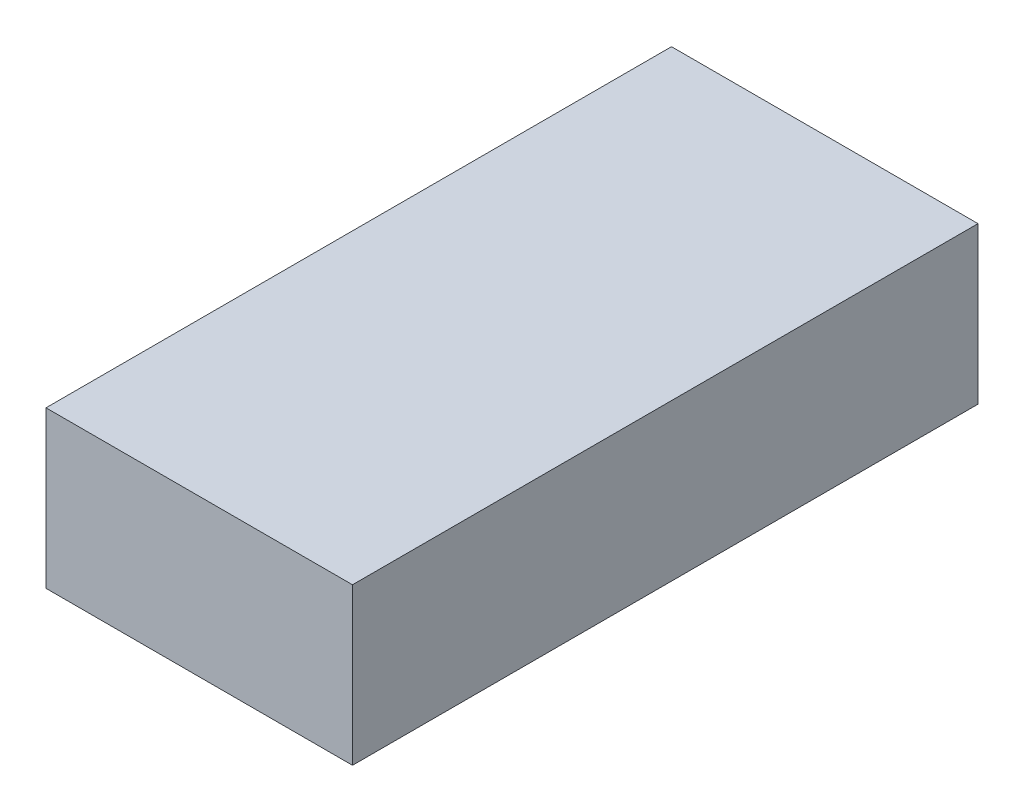
SolidWorks part; units mm, degrees
ref_plane "Спереди" through (0, 0, 0) normal (0, 0, 1) x (1, 0, 0)
ref_plane "Сверху" through (0, 0, 0) normal (0, 1, 0) x (1, 0, 0)
ref_plane "Справа" through (0, 0, 0) normal (1, 0, 0) x (0, 0, -1)
sketch "Эскиз1" plane through (0, 0, 0) normal (0, 0, 1) x (1, 0, 0)
  line L1 (-49, 25) -> (49, 25)
  line L2 (-49, 25) -> (-49, -25)
  line L3 (-49, -25) -> (49, -25)
  line L4 (49, 25) -> (49, -25)
  line L5 (-49, 25) -> (49, -25) construction
  line L6 (-49, -25) -> (49, 25) construction
  point P0 (0, 0)
  dimension "D1" = 98
  dimension "D2" = 50
extrude "База" add sketch "Эскиз1" along normal mid plane 200
hole_wizard "Отверстие обработанное метчиком M41" positions "Эскиз4" profile "Эскиз5" tap size "M4" standard "ISO"
sketch "Эскиз4" plane through (0, -25, 0) normal (0, -1, 0) x (-1, 0, 0)
  line L0 (25, -75) -> (0, -75) construction
  line L1 (0, -75) -> (-25, -75) construction
  line L2 (-25, -75) -> (-25, 0) construction
  line L3 (-25, 0) -> (-25, 75) construction
  point P0 (25, -75)
  point P2 (-25, -75)
  point P4 (-25, 75)
  point P6 (25, 75)
  dimension "D1" = 50
  dimension "D2" = 150
sketch "Эскиз5" plane through (-25, -25, 75) normal (1, 0, 0) x (0, 0, -1)
  line L0 (0, 0) -> (0, 12.4914)
  line L1 (0, 12.4914) -> (1.65, 11.5)
  line L2 (1.65, 11.5) -> (1.65, 0)
  line L5 (1.65, 0) -> (0, 0)
  line L10 (0, 12.4914) -> (-1.65, 11.5) construction
  line L11 (0, -6.35) -> (0, 107.95) construction
  dimension "Диаметр сверла" = 3.3
  dimension "Глубина сверла" = 11.5
  dimension "Угол заточки сверла" = 118
cosmetic thread "Отверстие резьбы1" parameters "D1"=8, "D2"=4
cosmetic thread "Отверстие резьбы2" parameters "D1"=8, "D2"=4
cosmetic thread "Отверстие резьбы3" parameters "D1"=8, "D2"=4
cosmetic thread "Отверстие резьбы4" parameters "D1"=8, "D2"=4
